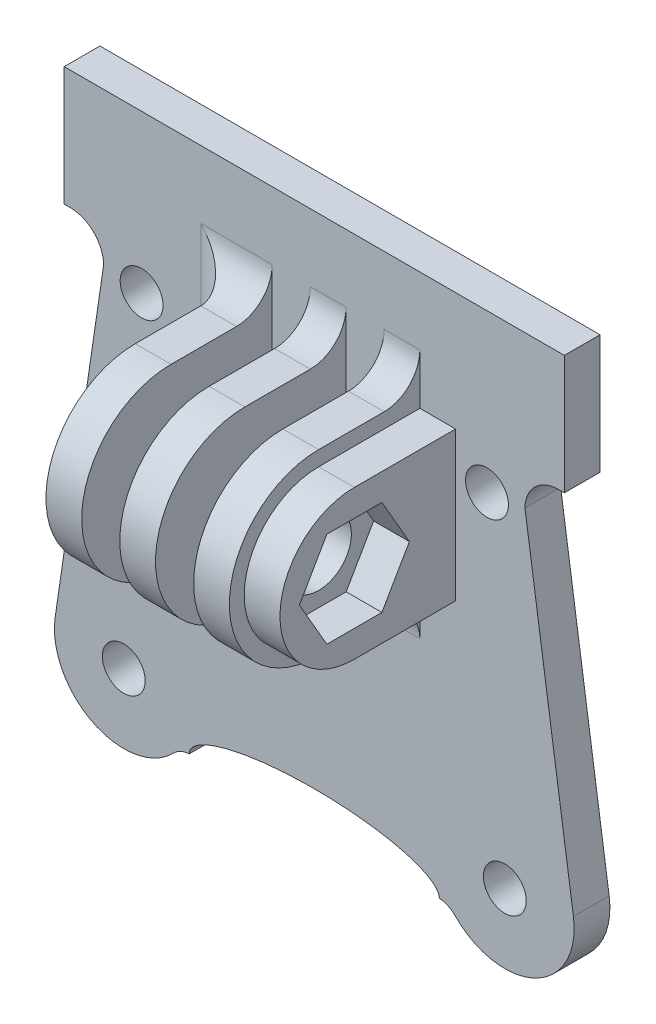
SolidWorks part; units mm, degrees
ref_plane "Front Plane" through (0, 0, 0) normal (0, 0, 1) x (1, 0, 0)
ref_plane "Top Plane" through (0, 0, 0) normal (0, 1, 0) x (1, 0, 0)
ref_plane "Right Plane" through (0, 0, 0) normal (1, 0, 0) x (0, 0, -1)
sketch "Sketch1" plane through (0, 0, 0) normal (0, 0, 1) x (1, 0, 0)
  line L7 (-22.1661, -51.053) -> (-21.6564, -51.053)
  line L8 (-18.8568, -53.8085) -> (-22.9291, -81.4839)
  line L9 (20.5968, -81.4839) -> (16.5245, -53.8085)
  line L10 (19.3242, -51.053) -> (19.8339, -51.053)
  line L11 (19.8339, -51.053) -> (19.8339, -41.053)
  line L12 (19.8339, -41.053) -> (-22.1661, -41.053)
  line L13 (-22.1661, -41.053) -> (-22.1661, -51.053)
  line L14 (-22.1661, -51.053) -> (-21.6564, -51.053)
  line L15 (-18.8568, -53.8085) -> (-22.9291, -81.4839)
  line L16 (20.5968, -81.4839) -> (16.5245, -53.8085)
  line L17 (19.3242, -51.053) -> (19.8339, -51.053)
  line L18 (19.8339, -51.053) -> (19.8339, -41.053)
  line L19 (19.8339, -41.053) -> (-22.1661, -41.053)
  line L20 (-22.1661, -41.053) -> (-22.1661, -51.053)
  circle A1 centre (-15.6661, -54.278) radius 1.8 construction
  circle A3 centre (-17.1661, -82.3318) radius 1.8 construction
  circle A5 centre (14.8339, -82.3318) radius 1.8 construction
  circle A6 centre (13.3339, -54.278) radius 1.8 construction
  circle A7 centre (-15.6661, -54.278) radius 1.8
  circle A8 centre (-17.1661, -82.3318) radius 1.8
  arc A9 (-18.8568, -53.8085) -> (-21.6564, -51.053) centre (-21.6564, -53.853) ccw
  arc A10 (-22.9291, -81.4839) -> (-12.9869, -86.3895) centre (-17.1661, -82.3318) ccw
  arc A11 (-11.6661, -85.786) -> (-12.9869, -86.3895) centre (-11.552, -87.7827) ccw
  arc A12 (10.6546, -86.3895) -> (9.3339, -85.786) centre (9.2197, -87.7827) ccw
  arc A13 (10.6546, -86.3895) -> (20.5968, -81.4839) centre (14.8339, -82.3318) ccw
  arc A14 (19.3242, -51.053) -> (16.5245, -53.8085) centre (19.3242, -53.853) ccw
  arc A15 (-18.8568, -53.8085) -> (-21.6564, -51.053) centre (-21.6564, -53.853) ccw
  arc A16 (-22.9291, -81.4839) -> (-12.9869, -86.3895) centre (-17.1661, -82.3318) ccw
  arc A17 (-11.6661, -85.786) -> (-12.9869, -86.3895) centre (-11.552, -87.7827) ccw
  arc A19 (10.6546, -86.3895) -> (9.3339, -85.786) centre (9.2197, -87.7827) ccw
  arc A20 (10.6546, -86.3895) -> (20.5968, -81.4839) centre (14.8339, -82.3318) ccw
  arc A21 (19.3242, -51.053) -> (16.5245, -53.8085) centre (19.3242, -53.853) ccw
  circle A22 centre (14.8339, -82.3318) radius 1.8
  circle A23 centre (13.3339, -54.278) radius 1.8
  ellipse E1 centre (-1.1661, -85.786) end of major axis (-11.6661, -85.786) minor radius 2.7176 (9.3339, -85.786) -> (-11.6661, -85.786) ccw
  ellipse E2 centre (-1.1661, -85.786) end of major axis (-11.6661, -85.786) minor radius 2.7176 (9.3339, -85.786) -> (-11.6661, -85.786) ccw
  dimension "D1" = 0
extrude "Boss-Extrude1" add sketch "Sketch1" along normal blind 3
sketch "Sketch2" plane through (0, 0, 3) normal (0, 0, 1) x (1, 0, 0)
  line L0 (0, -49.7212) -> (0, -83.0852) construction
  line L2 (-19.3589, -57.2212) -> (17.0267, -57.2212) construction
  line L3 (-1.5, -49.7212) -> (1.5, -49.7212)
  line L4 (-1.5, -49.7212) -> (-1.5, -64.7212)
  line L5 (-1.5, -64.7212) -> (1.5, -64.7212)
  line L6 (1.5, -49.7212) -> (1.5, -64.7212)
  line L7 (-1.5, -49.7212) -> (1.5, -64.7212) construction
  line L8 (-1.5, -64.7212) -> (1.5, -49.7212) construction
  line L11 (-18.8568, -53.8085) -> (-22.9291, -81.4839) construction
  line L12 (-7.7, -49.7212) -> (-4.7, -49.7212)
  line L13 (-7.7, -49.7212) -> (-7.7, -64.7212)
  line L14 (-7.7, -64.7212) -> (-4.7, -64.7212)
  line L15 (-4.7, -49.7212) -> (-4.7, -64.7212)
  line L16 (-7.7, -49.7212) -> (-4.7, -64.7212) construction
  line L17 (-7.7, -64.7212) -> (-4.7, -49.7212) construction
  line L18 (4.7, -49.7212) -> (7.7, -49.7212)
  line L19 (4.7, -49.7212) -> (4.7, -64.7212)
  line L20 (4.7, -64.7212) -> (7.7, -64.7212)
  line L21 (7.7, -49.7212) -> (7.7, -64.7212)
  line L22 (4.7, -49.7212) -> (7.7, -64.7212) construction
  line L23 (4.7, -64.7212) -> (7.7, -49.7212) construction
  line L24 (20.5968, -81.4839) -> (16.5245, -53.8085) construction
  ellipse E0 centre (-1.1661, -85.786) end of major axis (-11.6661, -85.786) minor radius 2.7176 (9.3339, -85.786) -> (-11.6661, -85.786) ccw construction
  point P12 (0, -57.2212)
  point P23 (-6.2, -57.2212)
  point P28 (6.2, -57.2212)
  dimension "D1" = 3
  dimension "D2" = 15
  dimension "D3" = 3
  dimension "D4" = 3
  dimension "D5" = 3.2
  dimension "D6" = 3.2
extrude "Boss-Extrude2" add sketch "Sketch2" along normal blind 16
sketch "Sketch3" plane through (7.7, 0, 0) normal (1, 0, 0) x (0, 0, -1)
  line L0 (-19, -57.2212) -> (-3, -57.2212) construction
  line L1 (-19, -64.7212) -> (-19, -49.7212) construction
  line L2 (-3, -64.7212) -> (-3, -49.7212) construction
  line L4 (-19, -64.7212) -> (-3, -64.7212) construction
  line L5 (-11.5, -49.7212) -> (-19, -49.7212)
  line L6 (-19, -49.7212) -> (-19, -64.7212)
  line L7 (-19, -64.7212) -> (-11.5, -64.7212)
  circle A0 centre (-11.5, -57.2212) radius 7.5
  circle A1 centre (-11.5, -57.2212) radius 2.75
  dimension "D1" = 5.5
extrude "Cut-Extrude1" cut sketch "Sketch3" against normal up to surface (15.4 mm away)
sketch "Sketch4" plane through (7.7, 0, 0) normal (1, 0, 0) x (0, 0, -1)
  line L0 (-11.5, -57.2212) -> (-3, -57.2212) construction
  line L1 (-6.8812, -57.2212) -> (-9.1906, -53.2212)
  line L2 (-9.1906, -53.2212) -> (-13.8094, -53.2212)
  line L3 (-13.8094, -53.2212) -> (-16.1188, -57.2212)
  line L4 (-16.1188, -57.2212) -> (-13.8094, -61.2212)
  line L5 (-13.8094, -61.2212) -> (-9.1906, -61.2212)
  line L6 (-9.1906, -61.2212) -> (-6.8812, -57.2212)
  line L7 (-3, -64.7212) -> (-3, -49.7212) construction
  line L8 (-11.5, -50.9712) -> (-3, -50.9712)
  line L9 (-11.5, -63.4712) -> (-3, -63.4712)
  line L10 (-3, -63.4712) -> (-3, -50.9712)
  circle A0 centre (-11.5, -57.2212) radius 4 construction
  circle A1 centre (-11.5, -57.2212) radius 6.25
  dimension "D2" = 12.5
  dimension "D1" = 8
extrude "Boss-Extrude3" add sketch "Sketch4" along normal blind 3
fillet "Fillet1" radius 3 7 edges at (6.2, -49.7212, 3) (0, -49.7212, 3) (-6.2, -49.7212, 3) (6.2, -64.7212, 3) (0, -64.7212, 3) (-6.2, -64.7212, 3) (-7.7, -57.2212, 3)
